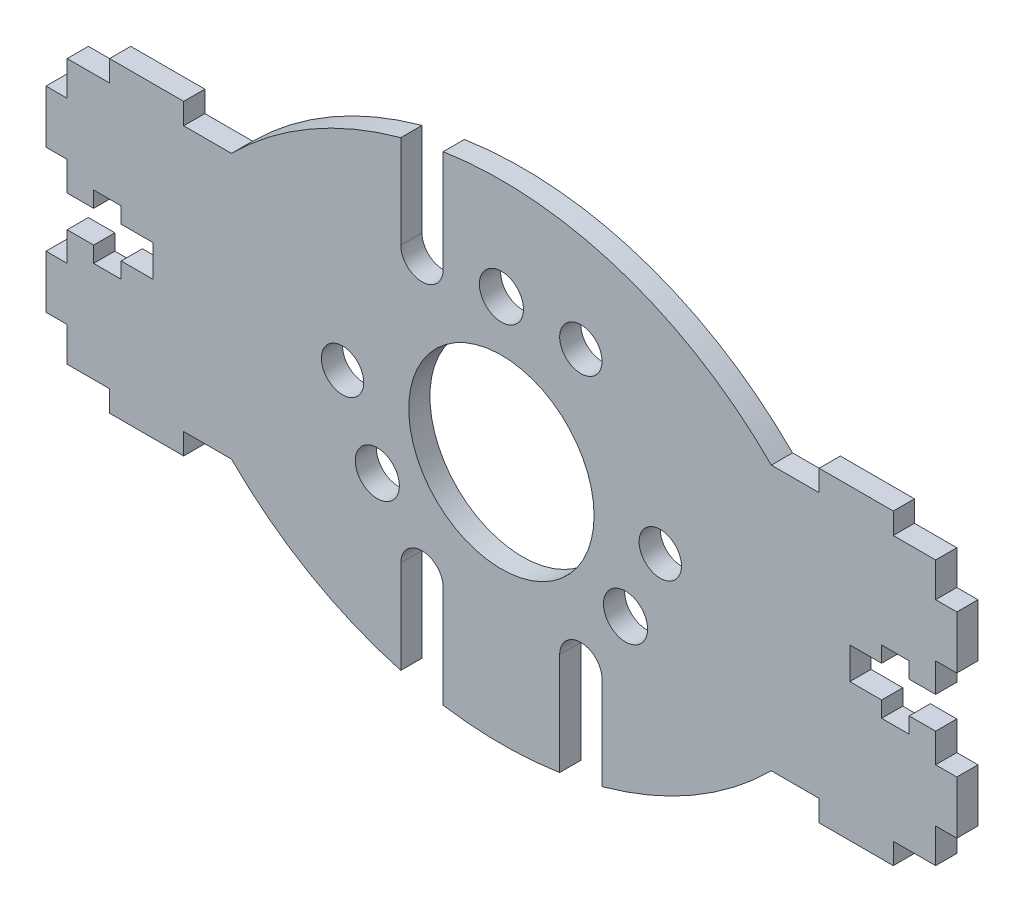
SolidWorks part; units mm, degrees
ref_plane "前视基准面" through (0, 0, 0) normal (0, 0, 1) x (1, 0, 0)
ref_plane "上视基准面" through (0, 0, 0) normal (0, 1, 0) x (1, 0, 0)
ref_plane "右视基准面" through (0, 0, 0) normal (1, 0, 0) x (0, 0, -1)
sketch "草图1" plane through (0, 0, 0) normal (0, 0, 1) x (1, 0, 0)
  line L368 (-41, 4.25) -> (-43, 4.25)
  line L369 (-43, 4.25) -> (-43, 9.25)
  line L370 (-43, 9.25) -> (-41, 9.25)
  line L371 (-41, 9.25) -> (-41, 12.5)
  line L376 (-37, 14.5) -> (-30, 14.5)
  line L378 (-30, 12.5) -> (-30, 14.5)
  line L379 (-37, 14.5) -> (-37, 12.5)
  line L380 (-37, 12.5) -> (-41, 12.5)
  line L399 (0, 0) -> (0, -2.02) construction
  line L405 (-38.5, -1.5) -> (-41, -1.5)
  line L406 (-38.5, 1.5) -> (-41, 1.5)
  line L407 (-38.5, -1.5) -> (-38.5, -3)
  line L408 (-32.9, 1.5) -> (-32.9, -1.5)
  line L409 (-38.5, 1.5) -> (-38.5, 3)
  line L410 (-38.5, -3) -> (-35.9, -3)
  line L411 (-35.9, -3) -> (-35.9, -1.5)
  line L412 (-35.9, -1.5) -> (-32.9, -1.5)
  line L413 (-35.9, 1.5) -> (-32.9, 1.5)
  line L414 (-35.9, 3) -> (-35.9, 1.5)
  line L415 (-38.5, 3) -> (-35.9, 3)
  line L417 (-41, 4.25) -> (-41, 1.5)
  line L418 (-32.9, 0) -> (-31.8185, 0) construction
  line L419 (-37, -12.5) -> (-41, -12.5)
  line L420 (-37, -14.5) -> (-37, -12.5)
  line L421 (-30, -12.5) -> (-30, -14.5)
  line L422 (-37, -14.5) -> (-30, -14.5)
  line L423 (-41, -9.25) -> (-41, -12.5)
  line L424 (-43, -9.25) -> (-41, -9.25)
  line L425 (-43, -4.25) -> (-43, -9.25)
  line L426 (-41, -4.25) -> (-43, -4.25)
  line L427 (-30, -12.5) -> (-25.489, -12.5)
  line L428 (-41, -1.5) -> (-41, -4.25)
  line L429 (32.9, 0) -> (31.8185, 0) construction
  line L430 (41, -1.5) -> (41, -4.25)
  line L431 (30, -12.5) -> (25.489, -12.5)
  line L432 (41, -4.25) -> (43, -4.25)
  line L434 (43, -9.25) -> (41, -9.25)
  line L435 (41, -9.25) -> (41, -12.5)
  line L436 (37, -14.5) -> (30, -14.5)
  line L437 (30, -12.5) -> (30, -14.5)
  line L438 (37, -14.5) -> (37, -12.5)
  line L439 (37, -12.5) -> (41, -12.5)
  line L440 (41, 4.25) -> (41, 1.5)
  line L441 (38.5, 3) -> (35.9, 3)
  line L442 (35.9, 3) -> (35.9, 1.5)
  line L443 (35.9, 1.5) -> (32.9, 1.5)
  line L444 (35.9, -1.5) -> (32.9, -1.5)
  line L445 (35.9, -3) -> (35.9, -1.5)
  line L446 (38.5, -3) -> (35.9, -3)
  line L447 (38.5, 1.5) -> (38.5, 3)
  line L448 (32.9, 1.5) -> (32.9, -1.5)
  line L449 (38.5, -1.5) -> (38.5, -3)
  line L450 (38.5, 1.5) -> (41, 1.5)
  line L451 (38.5, -1.5) -> (41, -1.5)
  line L452 (37, 12.5) -> (41, 12.5)
  line L453 (37, 14.5) -> (37, 12.5)
  line L454 (30, 12.5) -> (30, 14.5)
  line L455 (37, 14.5) -> (30, 14.5)
  line L456 (41, 9.25) -> (41, 12.5)
  line L457 (43, 9.25) -> (41, 9.25)
  line L458 (43, 4.25) -> (43, 9.25)
  line L459 (41, 4.25) -> (43, 4.25)
  line L460 (30, 12.5) -> (25.489, 12.5)
  line L463 (-30, 12.5) -> (-25.489, 12.5)
  line L464 (43, -9.25) -> (43, -4.25)
  line L465 (-9.5, -12.9904) -> (-9.5, -21.7835)
  line L466 (-5.5, -12.9904) -> (-5.5, -22.6358)
  line L467 (5.5, -12.9904) -> (5.5, -22.6358)
  line L468 (9.5, -12.9904) -> (9.5, -21.7835)
  line L471 (-5.5, 12.9904) -> (-5.5, 22.6358)
  line L472 (-9.5, 12.9904) -> (-9.5, 21.7835)
  circle A13 centre (0, 0) radius 15 construction
  circle A14 centre (0, 0) radius 13.53 construction
  circle A15 centre (-15, 0) radius 2
  circle A16 centre (-7.5, 12.9904) radius 2 construction
  circle A17 centre (7.5, 12.9904) radius 2
  circle A18 centre (15, 0) radius 2
  circle A19 centre (7.5, -12.9904) radius 2 construction
  circle A20 centre (-7.5, -12.9904) radius 2 construction
  circle A21 centre (0, 13.53) radius 2.08
  circle A22 centre (11.7173, -6.765) radius 2.08
  circle A23 centre (-11.7173, -6.765) radius 2.08
  circle A24 centre (0, 0) radius 8.75
  arc A25 (-25.489, 12.5) -> (25.489, 12.5) centre (0, -12.989) cw construction
  arc A26 (-25.489, -12.5) -> (25.489, -12.5) centre (0, 12.989) ccw construction
  arc A29 (-9.5, -12.9904) -> (-5.5, -12.9904) centre (-7.5, -12.9904) cw
  arc A30 (5.5, -12.9904) -> (9.5, -12.9904) centre (7.5, -12.9904) cw
  arc A31 (-25.489, -12.5) -> (-9.5, -21.7835) centre (0, 12.989) ccw
  arc A32 (5.5, -22.6358) -> (-5.5, -22.6358) centre (0, 12.989) cw
  arc A33 (9.5, -21.7835) -> (25.489, -12.5) centre (0, 12.989) ccw
  arc A37 (-25.489, 12.5) -> (-9.5, 21.7835) centre (0, -12.989) cw
  arc A38 (-5.5, 22.6358) -> (25.489, 12.5) centre (0, -12.989) cw
  arc A39 (-9.5, 12.9904) -> (-5.5, 12.9904) centre (-7.5, 12.9904) ccw
  dimension "D1" = 6
  dimension "D2" = 3
extrude "凸台-拉伸2" add sketch "草图1" along normal blind 2
sketch "草图2" plane through (-41, 0, 0) normal (-1, 0, 0) x (0, 0, 1)
  line L0 (1, 1.5) -> (1, -1.5)
  line L1 (2, 1.5) -> (0, 1.5) construction
  line L2 (2, -1.5) -> (0, -1.5) construction
  circle A0 centre (1, 0) radius 1.5
sketch "草图3" plane through (41, 0, 0) normal (1, 0, 0) x (0, 0, -1)
  line L0 (-1, 1.5) -> (-1, -1.5)
  line L1 (-2, 1.5) -> (0, 1.5) construction
  line L2 (-2, -1.5) -> (0, -1.5) construction
  circle A0 centre (-1, 0) radius 1.5
